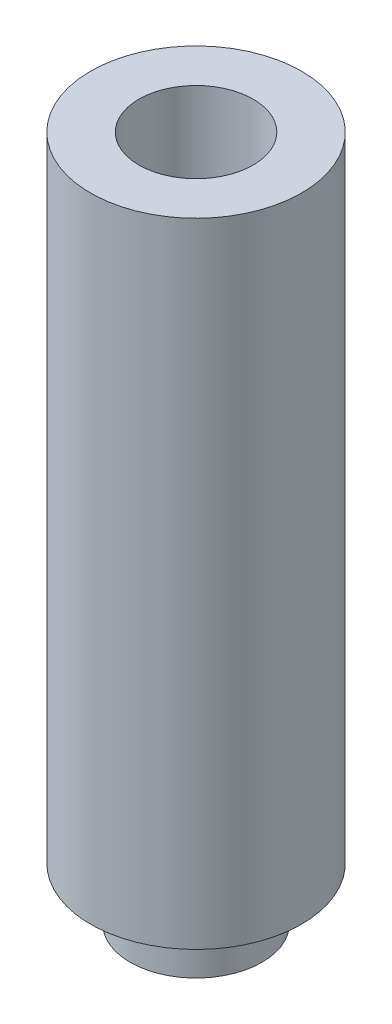
SolidWorks part; units mm, degrees
ref_plane "Front Plane" through (0, 0, 0) normal (0, 0, 1) x (1, 0, 0)
ref_plane "Top Plane" through (0, 0, 0) normal (0, 1, 0) x (1, 0, 0)
ref_plane "Right Plane" through (0, 0, 0) normal (1, 0, 0) x (0, 0, -1)
sketch "Sketch1" plane through (0, 0, 0) normal (0, 1, 0) x (1, 0, 0)
  circle A0 centre (0, 0) radius 2.54
  dimension "D1" = 5.08
extrude "Boss-Extrude1" add sketch "Sketch1" along normal blind 15.24
sketch "Sketch2" plane through (0, 15.24, 0) normal (0, 1, 0) x (1, 0, 0)
  circle A0 centre (0, 0) radius 1.375
  dimension "D1" = 2.75
extrude "Cut-Extrude1" cut sketch "Sketch2" against normal blind 12.7 contours A0
sketch "Sketch4" plane through (0, 0, 0) normal (0, -1, 0) x (1, 0, 0)
  circle A0 centre (0, 0) radius 1.5875
  dimension "D1" = 3.175
sketch "Sketch5" plane through (0, 0, 0) normal (0, -1, 0) x (1, 0, 0)
  circle A5 centre (0, 0) radius 1.375
extrude "Extrude-Thin1" add sketch "Sketch4" along normal blind 1.27 thin contours A0 thin type one direction reverse wall 0.254
